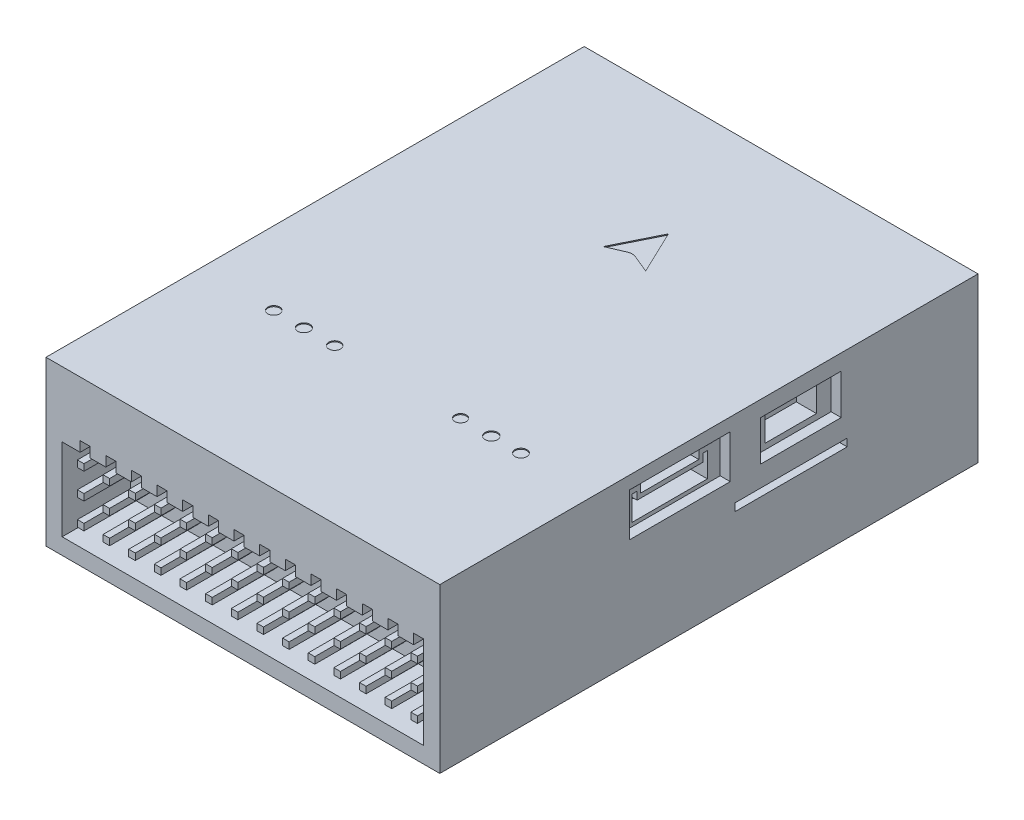
SolidWorks part; units mm, degrees
ref_plane "Front Plane" through (0, 0, 0) normal (0, 0, 1) x (1, 0, 0)
ref_plane "Top Plane" through (0, 0, 0) normal (0, 1, 0) x (1, 0, 0)
ref_plane "Right Plane" through (0, 0, 0) normal (1, 0, 0) x (0, 0, -1)
sketch "Sketch1" plane through (0, 0, 0) normal (0, 1, 0) x (1, 0, 0)
  line L0 (0, -55) -> (0, 55) construction
  line L1 (-19.5, -26.65) -> (19.5, -26.65)
  line L2 (-19.5, -26.65) -> (-19.5, 26.65)
  line L3 (-19.5, 26.65) -> (19.5, 26.65)
  line L4 (19.5, -26.65) -> (19.5, 26.65)
  line L5 (-55, 0) -> (55, 0) construction
  point P4 (0, 26.65)
  point P7 (19.5, 0)
  dimension "D1" = 39
  dimension "D2" = 53.3
extrude "Boss-Extrude1" add sketch "Sketch1" along normal mid plane 16.2
sketch "Sketch2" plane through (0, 0, 26.65) normal (0, 0, 1) x (1, 0, 0)
  line L0 (17.9, -6.5) -> (17.9, 2.64)
  line L1 (17.9, 2.64) -> (16.9, 2.64)
  line L2 (16.9, 2.64) -> (16.9, 1.64)
  line L3 (16.9, 1.64) -> (15.36, 1.64)
  line L4 (15.36, 1.64) -> (15.36, 2.64)
  line L5 (12.82, 1.64) -> (12.82, 2.64)
  line L6 (14.36, 1.64) -> (12.82, 1.64)
  line L7 (15.36, 2.64) -> (14.36, 2.64)
  line L8 (14.36, 2.64) -> (14.36, 1.64)
  line L9 (10.28, 1.64) -> (10.28, 2.64)
  line L10 (11.82, 1.64) -> (10.28, 1.64)
  line L11 (12.82, 2.64) -> (11.82, 2.64)
  line L12 (11.82, 2.64) -> (11.82, 1.64)
  line L13 (7.74, 1.64) -> (7.74, 2.64)
  line L14 (9.28, 1.64) -> (7.74, 1.64)
  line L15 (10.28, 2.64) -> (9.28, 2.64)
  line L16 (9.28, 2.64) -> (9.28, 1.64)
  line L17 (5.2, 1.64) -> (5.2, 2.64)
  line L18 (6.74, 1.64) -> (5.2, 1.64)
  line L19 (7.74, 2.64) -> (6.74, 2.64)
  line L20 (6.74, 2.64) -> (6.74, 1.64)
  line L21 (2.66, 1.64) -> (2.66, 2.64)
  line L22 (4.2, 1.64) -> (2.66, 1.64)
  line L23 (5.2, 2.64) -> (4.2, 2.64)
  line L24 (4.2, 2.64) -> (4.2, 1.64)
  line L25 (0.12, 1.64) -> (0.12, 2.64)
  line L26 (1.66, 1.64) -> (0.12, 1.64)
  line L27 (2.66, 2.64) -> (1.66, 2.64)
  line L28 (1.66, 2.64) -> (1.66, 1.64)
  line L29 (-2.42, 1.64) -> (-2.42, 2.64)
  line L30 (-0.88, 1.64) -> (-2.42, 1.64)
  line L31 (0.12, 2.64) -> (-0.88, 2.64)
  line L32 (-0.88, 2.64) -> (-0.88, 1.64)
  line L33 (-4.96, 1.64) -> (-4.96, 2.64)
  line L34 (-3.42, 1.64) -> (-4.96, 1.64)
  line L35 (-2.42, 2.64) -> (-3.42, 2.64)
  line L36 (-3.42, 2.64) -> (-3.42, 1.64)
  line L37 (-7.5, 1.64) -> (-7.5, 2.64)
  line L38 (-5.96, 1.64) -> (-7.5, 1.64)
  line L39 (-4.96, 2.64) -> (-5.96, 2.64)
  line L40 (-5.96, 2.64) -> (-5.96, 1.64)
  line L41 (-10.04, 1.64) -> (-10.04, 2.64)
  line L42 (-8.5, 1.64) -> (-10.04, 1.64)
  line L43 (-7.5, 2.64) -> (-8.5, 2.64)
  line L44 (-8.5, 2.64) -> (-8.5, 1.64)
  line L45 (-12.58, 1.64) -> (-12.58, 2.64)
  line L46 (-11.04, 1.64) -> (-12.58, 1.64)
  line L47 (-10.04, 2.64) -> (-11.04, 2.64)
  line L48 (-11.04, 2.64) -> (-11.04, 1.64)
  line L49 (-15.12, 1.64) -> (-15.12, 2.64)
  line L50 (-13.58, 1.64) -> (-15.12, 1.64)
  line L51 (-12.58, 2.64) -> (-13.58, 2.64)
  line L52 (-13.58, 2.64) -> (-13.58, 1.64)
  line L53 (17.9, -6.5) -> (-17.9, -6.5)
  line L54 (-16.12, 1.64) -> (-17.9, 1.64)
  line L55 (-15.12, 2.64) -> (-16.12, 2.64)
  line L56 (-16.12, 2.64) -> (-16.12, 1.64)
  line L57 (19.5, 8.1) -> (19.5, -8.1) construction
  line L58 (-17.66, 1.64) -> (-17.66, 2.64) [skipped]
  line L59 (-17.9, -6.5) -> (-17.9, 1.64)
  line L60 (49.3333, 77.9) -> (324.6667, 77.9) construction
  line L61 (-19.5, -8.1) -> (19.5, -8.1) construction
  dimension "D1" = 9.14
  dimension "D2" = 1
  dimension "D3" = 1.54
  dimension "D5" = 1.6
  dimension "D6" = 35.8
  dimension "1.5" = 1.6
  dimension "D4" = 14
extrude "Cut-Extrude1" cut sketch "Sketch2" against normal blind 6.75
sketch "Sketch3" plane through (0, 0, 19.9) normal (0, 0, 1) x (1, 0, 0)
  line L0 (49.3333, 77.9) -> (324.6667, 77.9) construction
  line L1 (-16.85, 0.39) -> (-16.2, 0.39)
  line L2 (-16.85, 0.39) -> (-16.85, -0.26)
  line L3 (-16.85, -0.26) -> (-16.2, -0.26)
  line L4 (-16.2, 0.39) -> (-16.2, -0.26)
  line L5 (-16.12, 1.64) -> (-17.9, 1.64) construction
  line L6 (-17.9, 1.64) -> (-17.9, -6.5) construction
  line L7 (-14.31, 0.39) -> (-14.31, -0.26)
  line L8 (-14.31, 0.39) -> (-13.66, 0.39)
  line L9 (-13.66, 0.39) -> (-13.66, -0.26)
  line L10 (-14.31, -0.26) -> (-13.66, -0.26)
  line L11 (-11.77, 0.39) -> (-11.77, -0.26)
  line L12 (-11.77, 0.39) -> (-11.12, 0.39)
  line L13 (-11.12, 0.39) -> (-11.12, -0.26)
  line L14 (-11.77, -0.26) -> (-11.12, -0.26)
  line L15 (-9.23, 0.39) -> (-9.23, -0.26)
  line L16 (-9.23, 0.39) -> (-8.58, 0.39)
  line L17 (-8.58, 0.39) -> (-8.58, -0.26)
  line L18 (-9.23, -0.26) -> (-8.58, -0.26)
  line L19 (-6.69, 0.39) -> (-6.69, -0.26)
  line L20 (-6.69, 0.39) -> (-6.04, 0.39)
  line L21 (-6.04, 0.39) -> (-6.04, -0.26)
  line L22 (-6.69, -0.26) -> (-6.04, -0.26)
  line L23 (-4.15, 0.39) -> (-4.15, -0.26)
  line L24 (-4.15, 0.39) -> (-3.5, 0.39)
  line L25 (-3.5, 0.39) -> (-3.5, -0.26)
  line L26 (-4.15, -0.26) -> (-3.5, -0.26)
  line L27 (-1.61, 0.39) -> (-1.61, -0.26)
  line L28 (-1.61, 0.39) -> (-0.96, 0.39)
  line L29 (-0.96, 0.39) -> (-0.96, -0.26)
  line L30 (-1.61, -0.26) -> (-0.96, -0.26)
  line L31 (0.93, 0.39) -> (0.93, -0.26)
  line L32 (0.93, 0.39) -> (1.58, 0.39)
  line L33 (1.58, 0.39) -> (1.58, -0.26)
  line L34 (0.93, -0.26) -> (1.58, -0.26)
  line L35 (3.47, 0.39) -> (3.47, -0.26)
  line L36 (3.47, 0.39) -> (4.12, 0.39)
  line L37 (4.12, 0.39) -> (4.12, -0.26)
  line L38 (3.47, -0.26) -> (4.12, -0.26)
  line L39 (6.01, 0.39) -> (6.01, -0.26)
  line L40 (6.01, 0.39) -> (6.66, 0.39)
  line L41 (6.66, 0.39) -> (6.66, -0.26)
  line L42 (6.01, -0.26) -> (6.66, -0.26)
  line L43 (8.55, 0.39) -> (8.55, -0.26)
  line L44 (8.55, 0.39) -> (9.2, 0.39)
  line L45 (9.2, 0.39) -> (9.2, -0.26)
  line L46 (8.55, -0.26) -> (9.2, -0.26)
  line L47 (11.09, 0.39) -> (11.09, -0.26)
  line L48 (11.09, 0.39) -> (11.74, 0.39)
  line L49 (11.74, 0.39) -> (11.74, -0.26)
  line L50 (11.09, -0.26) -> (11.74, -0.26)
  line L51 (13.63, 0.39) -> (13.63, -0.26)
  line L52 (13.63, 0.39) -> (14.28, 0.39)
  line L53 (14.28, 0.39) -> (14.28, -0.26)
  line L54 (13.63, -0.26) -> (14.28, -0.26)
  line L55 (16.17, 0.39) -> (16.17, -0.26)
  line L56 (16.17, 0.39) -> (16.82, 0.39)
  line L57 (16.82, 0.39) -> (16.82, -0.26)
  line L58 (16.17, -0.26) -> (16.82, -0.26)
  line L59 (-14.31, -2.17) -> (-14.31, -2.82)
  line L60 (-14.31, -2.17) -> (-13.66, -2.17)
  line L61 (-13.66, -2.17) -> (-13.66, -2.82)
  line L62 (-14.31, -2.82) -> (-13.66, -2.82)
  line L63 (-11.77, -2.17) -> (-11.77, -2.82)
  line L64 (-11.77, -2.17) -> (-11.12, -2.17)
  line L65 (-11.12, -2.17) -> (-11.12, -2.82)
  line L66 (-11.77, -2.82) -> (-11.12, -2.82)
  line L67 (-9.23, -2.17) -> (-9.23, -2.82)
  line L68 (-9.23, -2.17) -> (-8.58, -2.17)
  line L69 (-8.58, -2.17) -> (-8.58, -2.82)
  line L70 (-9.23, -2.82) -> (-8.58, -2.82)
  line L71 (-6.69, -2.17) -> (-6.69, -2.82)
  line L72 (-6.69, -2.17) -> (-6.04, -2.17)
  line L73 (-6.04, -2.17) -> (-6.04, -2.82)
  line L74 (-6.69, -2.82) -> (-6.04, -2.82)
  line L75 (-4.15, -2.17) -> (-4.15, -2.82)
  line L76 (-4.15, -2.17) -> (-3.5, -2.17)
  line L77 (-3.5, -2.17) -> (-3.5, -2.82)
  line L78 (-4.15, -2.82) -> (-3.5, -2.82)
  line L79 (-1.61, -2.17) -> (-1.61, -2.82)
  line L80 (-1.61, -2.17) -> (-0.96, -2.17)
  line L81 (-0.96, -2.17) -> (-0.96, -2.82)
  line L82 (-1.61, -2.82) -> (-0.96, -2.82)
  line L83 (0.93, -2.17) -> (0.93, -2.82)
  line L84 (0.93, -2.17) -> (1.58, -2.17)
  line L85 (1.58, -2.17) -> (1.58, -2.82)
  line L86 (0.93, -2.82) -> (1.58, -2.82)
  line L87 (3.47, -2.17) -> (3.47, -2.82)
  line L88 (3.47, -2.17) -> (4.12, -2.17)
  line L89 (4.12, -2.17) -> (4.12, -2.82)
  line L90 (3.47, -2.82) -> (4.12, -2.82)
  line L91 (6.01, -2.17) -> (6.01, -2.82)
  line L92 (6.01, -2.17) -> (6.66, -2.17)
  line L93 (6.66, -2.17) -> (6.66, -2.82)
  line L94 (6.01, -2.82) -> (6.66, -2.82)
  line L95 (8.55, -2.17) -> (8.55, -2.82)
  line L96 (8.55, -2.17) -> (9.2, -2.17)
  line L97 (9.2, -2.17) -> (9.2, -2.82)
  line L98 (8.55, -2.82) -> (9.2, -2.82)
  line L99 (11.09, -2.17) -> (11.09, -2.82)
  line L100 (11.09, -2.17) -> (11.74, -2.17)
  line L101 (11.74, -2.17) -> (11.74, -2.82)
  line L102 (11.09, -2.82) -> (11.74, -2.82)
  line L103 (13.63, -2.17) -> (13.63, -2.82)
  line L104 (13.63, -2.17) -> (14.28, -2.17)
  line L105 (14.28, -2.17) -> (14.28, -2.82)
  line L106 (13.63, -2.82) -> (14.28, -2.82)
  line L107 (16.17, -2.17) -> (16.17, -2.82)
  line L108 (16.17, -2.17) -> (16.82, -2.17)
  line L109 (16.82, -2.17) -> (16.82, -2.82)
  line L110 (16.17, -2.82) -> (16.82, -2.82)
  line L111 (-14.31, -4.73) -> (-14.31, -5.38)
  line L112 (-14.31, -4.73) -> (-13.66, -4.73)
  line L113 (-13.66, -4.73) -> (-13.66, -5.38)
  line L114 (-14.31, -5.38) -> (-13.66, -5.38)
  line L115 (-11.77, -4.73) -> (-11.77, -5.38)
  line L116 (-11.77, -4.73) -> (-11.12, -4.73)
  line L117 (-11.12, -4.73) -> (-11.12, -5.38)
  line L118 (-11.77, -5.38) -> (-11.12, -5.38)
  line L119 (-9.23, -4.73) -> (-9.23, -5.38)
  line L120 (-9.23, -4.73) -> (-8.58, -4.73)
  line L121 (-8.58, -4.73) -> (-8.58, -5.38)
  line L122 (-9.23, -5.38) -> (-8.58, -5.38)
  line L123 (-6.69, -4.73) -> (-6.69, -5.38)
  line L124 (-6.69, -4.73) -> (-6.04, -4.73)
  line L125 (-6.04, -4.73) -> (-6.04, -5.38)
  line L126 (-6.69, -5.38) -> (-6.04, -5.38)
  line L127 (-4.15, -4.73) -> (-4.15, -5.38)
  line L128 (-4.15, -4.73) -> (-3.5, -4.73)
  line L129 (-3.5, -4.73) -> (-3.5, -5.38)
  line L130 (-4.15, -5.38) -> (-3.5, -5.38)
  line L131 (-1.61, -4.73) -> (-1.61, -5.38)
  line L132 (-1.61, -4.73) -> (-0.96, -4.73)
  line L133 (-0.96, -4.73) -> (-0.96, -5.38)
  line L134 (-1.61, -5.38) -> (-0.96, -5.38)
  line L135 (0.93, -4.73) -> (0.93, -5.38)
  line L136 (0.93, -4.73) -> (1.58, -4.73)
  line L137 (1.58, -4.73) -> (1.58, -5.38)
  line L138 (0.93, -5.38) -> (1.58, -5.38)
  line L139 (3.47, -4.73) -> (3.47, -5.38)
  line L140 (3.47, -4.73) -> (4.12, -4.73)
  line L141 (4.12, -4.73) -> (4.12, -5.38)
  line L142 (3.47, -5.38) -> (4.12, -5.38)
  line L143 (6.01, -4.73) -> (6.01, -5.38)
  line L144 (6.01, -4.73) -> (6.66, -4.73)
  line L145 (6.66, -4.73) -> (6.66, -5.38)
  line L146 (6.01, -5.38) -> (6.66, -5.38)
  line L147 (8.55, -4.73) -> (8.55, -5.38)
  line L148 (8.55, -4.73) -> (9.2, -4.73)
  line L149 (9.2, -4.73) -> (9.2, -5.38)
  line L150 (8.55, -5.38) -> (9.2, -5.38)
  line L151 (11.09, -4.73) -> (11.09, -5.38)
  line L152 (11.09, -4.73) -> (11.74, -4.73)
  line L153 (11.74, -4.73) -> (11.74, -5.38)
  line L154 (11.09, -5.38) -> (11.74, -5.38)
  line L155 (13.63, -4.73) -> (13.63, -5.38)
  line L156 (13.63, -4.73) -> (14.28, -4.73)
  line L157 (14.28, -4.73) -> (14.28, -5.38)
  line L158 (13.63, -5.38) -> (14.28, -5.38)
  line L159 (16.17, -4.73) -> (16.17, -5.38)
  line L160 (16.17, -4.73) -> (16.82, -4.73)
  line L161 (16.82, -4.73) -> (16.82, -5.38)
  line L162 (16.17, -5.38) -> (16.82, -5.38)
  line L163 (-16.85, -2.17) -> (-16.85, -2.82)
  line L164 (-16.85, -2.17) -> (-16.2, -2.17)
  line L165 (-16.2, -2.17) -> (-16.2, -2.82)
  line L166 (-16.85, -2.82) -> (-16.2, -2.82)
  line L167 (-16.85, -4.73) -> (-16.85, -5.38)
  line L168 (-16.85, -4.73) -> (-16.2, -4.73)
  line L169 (-16.2, -4.73) -> (-16.2, -5.38)
  line L170 (-16.85, -5.38) -> (-16.2, -5.38)
  dimension "D1" = 0.65
  dimension "D2" = 0.65
  dimension "D3" = 1.25
  dimension "D4" = 1.05
  dimension "D5" = 14
  dimension "D6" = 3
extrude "Boss-Extrude2" add sketch "Sketch3" along normal offset from surface (6.29 mm away) 0.46 up to face at (0.2421, 1.8421, 26.65)
sketch "Sketch4" plane through (-19.5, 0, 0) normal (-1, 0, 0) x (0, 0, 1)
  line L0 (-255.35, 20.7333) -> (-255.35, 136.0667) construction
  line L1 (-13.428, 3.9516) -> (-6.9161, 3.9516) construction
  line L2 (-13.428, 5.2953) -> (-6.9161, 5.2953)
  line L3 (-13.428, 2.6079) -> (-6.9161, 2.6079)
  line L4 (6.6652, -1.568) -> (7.1925, -1.568)
  line L5 (-2.12, 6.3083) -> (-1.0864, 6.3083)
  line L6 (-2.12, 6.3083) -> (-2.12, 5.8535)
  line L7 (-2.12, 5.8535) -> (-1.0864, 5.8535)
  line L8 (-1.0864, 6.3083) -> (-1.0864, 5.8535)
  line L9 (6.5832, 6.3083) -> (7.6375, 6.3083)
  line L10 (6.5832, 6.3083) -> (6.5832, 5.8535)
  line L11 (6.5832, 5.8535) -> (7.6375, 5.8535)
  line L12 (7.6375, 6.3083) -> (7.6375, 5.8535)
  line L13 (-1.6032, 5.2953) -> (-1.0864, 5.2953)
  line L14 (-1.6032, 5.2953) -> (-1.6032, 2.8973)
  line L15 (-1.6032, 2.8973) -> (7.1103, 2.8973)
  line L16 (7.1103, 5.2953) -> (7.1103, 2.8973)
  line L17 (0.4641, -2.0021) -> (1.3737, -2.0021)
  line L18 (0.4641, -2.0021) -> (0.4641, -2.5189)
  line L19 (0.4641, -2.5189) -> (1.3737, -2.5189)
  line L20 (1.3737, -2.0021) -> (1.3737, -2.5189)
  line L21 (6.5832, -2.0021) -> (7.6375, -2.0021)
  line L22 (6.5832, -2.0021) -> (6.5832, -2.5189)
  line L23 (6.5832, -2.5189) -> (7.6375, -2.5189)
  line L24 (7.6375, -2.0021) -> (7.6375, -2.5189)
  line L33 (-14.2135, 1.1815) -> (-6.1305, 1.1815)
  line L34 (-14.2135, 1.1815) -> (-14.2135, -1.568)
  line L35 (-14.2135, -1.568) -> (-6.1305, -1.568)
  line L36 (-6.1305, 1.1815) -> (-6.1305, -1.568)
  line L41 (0.8703, -1.568) -> (1.3737, -1.568)
  line L42 (0.8703, -1.568) -> (0.8703, 0.8518)
  line L43 (0.8703, 0.8518) -> (7.1925, 0.8518)
  line L44 (7.1925, -1.568) -> (7.1925, 0.8518)
  line L45 (6.6652, -1.2126) -> (1.3737, -1.2126)
  line L46 (6.6652, -1.2126) -> (6.6652, -1.568)
  line L48 (1.3737, -1.2126) -> (1.3737, -1.568)
  line L49 (6.6652, 5.2953) -> (7.1103, 5.2953)
  line L50 (1.7567, -1.568) -> (6.2893, -1.568)
  line L51 (1.7567, -1.568) -> (1.7567, -2.5189)
  line L52 (1.7567, -2.5189) -> (6.2893, -2.5189)
  line L53 (6.2893, -1.568) -> (6.2893, -2.5189)
  line L55 (-1.0864, 5.2953) -> (-1.0864, 4.5845)
  line L56 (-1.0864, 4.5845) -> (6.6652, 4.5845)
  line L57 (6.6652, 5.2953) -> (6.6652, 4.5845)
  line L59 (-0.7633, 6.3083) -> (6.2893, 6.3083)
  line L60 (-0.7633, 6.3083) -> (-0.7633, 4.9703)
  line L61 (-0.7633, 4.9703) -> (6.2893, 4.9703)
  line L62 (6.2893, 6.3083) -> (6.2893, 4.9703)
  arc A0 (-13.428, 5.2953) -> (-13.428, 2.6079) centre (-13.428, 3.9516) ccw
  arc A1 (-6.9161, 2.6079) -> (-6.9161, 5.2953) centre (-6.9161, 3.9516) ccw
  point P4 (-10.172, 3.9516)
extrude "Cut-Extrude2" cut sketch "Sketch4" against normal blind 3
sketch "Sketch5" plane through (-19.5, 0, 0) normal (-1, 0, 0) x (0, 0, 1)
  line L1 (-2.8495, 6.7236) -> (8.3927, 6.7236)
  line L2 (-2.8495, 6.7236) -> (-2.8495, 2.4746)
  line L3 (-2.8495, 2.4746) -> (8.3927, 2.4746)
  line L4 (8.3927, 6.7236) -> (8.3927, 2.4746)
  line L5 (-0.3045, -3.0801) -> (8.3927, -3.0801)
  line L6 (-0.3045, -3.0801) -> (-0.3045, 1.2575)
  line L7 (-0.3045, 1.2575) -> (8.3927, 1.2575)
  line L8 (8.3927, -3.0801) -> (8.3927, 1.2575)
extrude "Cut-Extrude3" cut sketch "Sketch5" against normal blind 1
sketch "Sketch6" plane through (-16.5, 0, 0) normal (-1, 0, 0) x (0, 0, 1)
  line L0 (-13.1411, 3.9516) -> (-7.1421, 3.9516) construction
  line L1 (-13.428, 3.9516) -> (-6.9161, 3.9516) construction
  line L2 (-13.1411, 4.4327) -> (-7.1421, 4.4327)
  line L3 (-13.1411, 3.4706) -> (-7.1421, 3.4706)
  arc A0 (-13.1411, 4.4327) -> (-13.1411, 3.4706) centre (-13.1411, 3.9516) ccw
  arc A1 (-7.1421, 3.4706) -> (-7.1421, 4.4327) centre (-7.1421, 3.9516) ccw
  point P4 (-10.1416, 3.9516)
extrude "Boss-Extrude3" add sketch "Sketch6" along normal blind 2
sketch "Sketch7" plane through (19.5, 0, 0) normal (1, 0, 0) x (0, 0, -1)
  line L0 (255.35, -20.7333) -> (255.35, -136.0667) construction
  line L1 (0.4015, 5.3443) -> (0.8484, 5.3443)
  line L2 (-7.1427, 6.2913) -> (-6.1106, 6.2913)
  line L3 (-7.1427, 6.2913) -> (-7.1427, 5.8231)
  line L4 (-7.1427, 5.8231) -> (-6.1106, 5.8231)
  line L5 (-6.1106, 6.2913) -> (-6.1106, 5.8231)
  line L6 (-6.6266, 5.3443) -> (-6.1106, 5.3443)
  line L7 (-6.6266, 5.3443) -> (-6.6266, 2.9182)
  line L8 (-6.6266, 2.9182) -> (0.8484, 2.9182)
  line L9 (0.8484, 5.3443) -> (0.8484, 2.9182)
  line L10 (0.4015, 6.2913) -> (1.3592, 6.2913)
  line L11 (0.4015, 6.2913) -> (0.4015, 5.8231)
  line L12 (0.4015, 5.8231) -> (1.3592, 5.8231)
  line L13 (1.3592, 6.2913) -> (1.3592, 5.8231)
  line L15 (-6.1106, 5.3443) -> (-6.1106, 4.5675)
  line L16 (-6.1106, 4.5675) -> (0.4015, 4.5675)
  line L17 (0.4015, 5.3443) -> (0.4015, 4.5675)
  line L19 (-5.7701, 6.2913) -> (0, 6.2913)
  line L20 (-5.7701, 6.2913) -> (-5.7701, 5.0038)
  line L21 (-5.7701, 5.0038) -> (0, 5.0038)
  line L22 (0, 6.2913) -> (0, 5.0038)
  line L23 (6.5497, 5.8231) -> (11.6552, 5.8231)
  line L24 (6.5497, 5.8231) -> (6.5497, 3.117)
  line L25 (6.5497, 3.117) -> (11.6552, 3.117)
  line L26 (11.6552, 5.8231) -> (11.6552, 3.117)
  line L27 (2.5929, 0.4917) -> (13.6989, 0.4917)
  line L28 (2.5929, 0.4917) -> (2.5929, -0.2598)
  line L29 (2.5929, -0.2598) -> (13.6989, -0.2598)
  line L30 (13.6989, 0.4917) -> (13.6989, -0.2598)
extrude "Cut-Extrude4" cut sketch "Sketch7" against normal blind 3
sketch "Sketch8" plane through (19.5, 0, 0) normal (1, 0, 0) x (0, 0, -1)
  line L1 (-7.8864, 6.8306) -> (2.1133, 6.8306)
  line L2 (-7.8864, 6.8306) -> (-7.8864, 2.5486)
  line L3 (-7.8864, 2.5486) -> (2.1133, 2.5486)
  line L4 (2.1133, 6.8306) -> (2.1133, 2.5486)
  line L5 (5.1132, 6.5357) -> (13.1001, 6.5357)
  line L6 (5.1132, 6.5357) -> (5.1132, 2.5486)
  line L7 (5.1132, 2.5486) -> (13.1001, 2.5486)
  line L8 (13.1001, 6.5357) -> (13.1001, 2.5486)
extrude "Cut-Extrude5" cut sketch "Sketch8" against normal blind 1
sketch "Sketch9" plane through (0, 0, -26.65) normal (0, 0, -1) x (-1, 0, 0)
  line L0 (-49.3333, -78.4) -> (-324.6667, -78.4) construction
  line L1 (15.5763, 5.3359) -> (16.0761, 5.3359)
  line L2 (-16.5738, 6.2583) -> (-15.558, 6.2583)
  line L3 (-16.5738, 6.2583) -> (-16.5738, 5.8345)
  line L4 (-16.5738, 5.8345) -> (-15.558, 5.8345)
  line L5 (-15.558, 6.2583) -> (-15.558, 5.8345)
  line L6 (-10.3698, 6.2583) -> (-9.3468, 6.2583)
  line L7 (-10.3698, 6.2583) -> (-10.3698, 5.8345)
  line L8 (-10.3698, 5.8345) -> (-9.3468, 5.8345)
  line L9 (-9.3468, 6.2583) -> (-9.3468, 5.8345)
  line L10 (-7.3811, 6.2583) -> (-6.3215, 6.2583)
  line L11 (-7.3811, 6.2583) -> (-7.3811, 5.8345)
  line L12 (-7.3811, 5.8345) -> (-6.3215, 5.8345)
  line L13 (-6.3215, 6.2583) -> (-6.3215, 5.8345)
  line L14 (-1.1347, 6.2583) -> (-0.083, 6.2583)
  line L15 (-1.1347, 6.2583) -> (-1.1347, 5.8345)
  line L16 (-1.1347, 5.8345) -> (-0.083, 5.8345)
  line L17 (-0.083, 6.2583) -> (-0.083, 5.8345)
  line L18 (1.9225, 6.2583) -> (2.8641, 6.2583)
  line L19 (1.9225, 6.2583) -> (1.9225, 5.8345)
  line L20 (1.9225, 5.8345) -> (2.8641, 5.8345)
  line L21 (2.8641, 6.2583) -> (2.8641, 5.8345)
  line L22 (15.6474, 6.2583) -> (16.5795, 6.2583)
  line L23 (15.6474, 6.2583) -> (15.6474, 5.8345)
  line L24 (15.6474, 5.8345) -> (16.5795, 5.8345)
  line L25 (16.5795, 6.2583) -> (16.5795, 5.8345)
  line L26 (-16.5738, -2.0526) -> (-15.558, -2.0526)
  line L27 (-16.5738, -2.0526) -> (-16.5738, -2.4876)
  line L28 (-16.5738, -2.4876) -> (-15.558, -2.4876)
  line L29 (-15.558, -2.0526) -> (-15.558, -2.4876)
  line L30 (-7.8191, -2.0526) -> (-6.8513, -2.0526)
  line L31 (-7.8191, -2.0526) -> (-7.8191, -2.4876)
  line L32 (-7.8191, -2.4876) -> (-6.8513, -2.4876)
  line L33 (-6.8513, -2.0526) -> (-6.8513, -2.4876)
  line L34 (-4.8159, -2.0526) -> (-3.8631, -2.0526)
  line L35 (-4.8159, -2.0526) -> (-4.8159, -2.4876)
  line L36 (-4.8159, -2.4876) -> (-3.8631, -2.4876)
  line L37 (-3.8631, -2.0526) -> (-3.8631, -2.4876)
  line L38 (3.9038, -2.0526) -> (4.898, -2.0526)
  line L39 (3.9038, -2.0526) -> (3.9038, -2.4876)
  line L40 (3.9038, -2.4876) -> (4.898, -2.4876)
  line L41 (4.898, -2.0526) -> (4.898, -2.4876)
  line L42 (6.8449, -2.0526) -> (7.8391, -2.0526)
  line L43 (6.8449, -2.0526) -> (6.8449, -2.4876)
  line L44 (6.8449, -2.4876) -> (7.8391, -2.4876)
  line L45 (7.8391, -2.0526) -> (7.8391, -2.4876)
  line L46 (15.6474, -2.0526) -> (16.5795, -2.0526)
  line L47 (15.6474, -2.0526) -> (15.6474, -2.4876)
  line L48 (15.6474, -2.4876) -> (16.5795, -2.4876)
  line L49 (16.5795, -2.0526) -> (16.5795, -2.4876)
  line L50 (-16.0659, 5.2794) -> (-15.558, 5.2794)
  line L51 (-16.0659, 5.2794) -> (-16.0659, 2.9389)
  line L52 (-16.0659, 2.9389) -> (-9.8583, 2.9389)
  line L53 (-9.8583, 5.2794) -> (-9.8583, 2.9389)
  line L55 (-15.558, 5.2794) -> (-15.558, 4.6342)
  line L56 (-15.558, 4.6342) -> (-10.3698, 4.6342)
  line L57 (-10.3698, 5.2794) -> (-10.3698, 4.6342)
  line L58 (-6.8513, 5.3359) -> (-6.3215, 5.3359)
  line L59 (-6.8513, 5.3359) -> (-6.8513, 2.9389)
  line L60 (-6.8513, 2.9389) -> (-0.6088, 2.9389)
  line L61 (-0.6088, 5.3359) -> (-0.6088, 2.9389)
  line L63 (-6.3215, 5.3359) -> (-6.3215, 4.5853)
  line L64 (-6.3215, 4.5853) -> (-1.1347, 4.5853)
  line L65 (-1.1347, 5.3359) -> (-1.1347, 4.5853)
  line L66 (-16.0659, 0.8904) -> (-7.3352, 0.8904)
  line L67 (-16.0659, 0.8904) -> (-16.0659, -1.5854)
  line L68 (-16.0659, -1.5854) -> (-15.558, -1.5854)
  line L69 (-7.3352, 0.8904) -> (-7.3352, -1.5854)
  line L71 (-15.558, -1.5854) -> (-15.558, -0.8081)
  line L72 (-15.558, -0.8081) -> (-7.8191, -0.8081)
  line L73 (-7.8191, -1.5854) -> (-7.8191, -0.8081)
  line L74 (-4.3395, 0.8904) -> (4.4009, 0.8904)
  line L75 (-4.3395, 0.8904) -> (-4.3395, -1.5854)
  line L76 (-4.3395, -1.5854) -> (-3.8631, -1.5854)
  line L77 (4.4009, 0.8904) -> (4.4009, -1.5854)
  line L78 (-3.8631, -0.8081) -> (3.9038, -0.8081)
  line L79 (-3.8631, -0.8081) -> (-3.8631, -1.5854)
  line L81 (3.9038, -0.8081) -> (3.9038, -1.5854)
  line L82 (2.3588, 5.3359) -> (2.8641, 5.3359)
  line L83 (2.3588, 5.3359) -> (2.3588, 2.9389)
  line L84 (2.3588, 2.9389) -> (16.0761, 2.9389)
  line L85 (16.0761, 5.3359) -> (16.0761, 2.9389)
  line L87 (2.8641, 5.3359) -> (2.8641, 4.5853)
  line L88 (2.8641, 4.5853) -> (15.5763, 4.5853)
  line L89 (15.5763, 5.3359) -> (15.5763, 4.5853)
  line L90 (7.3755, -1.5854) -> (7.8391, -1.5854)
  line L91 (7.3755, -1.5854) -> (7.3755, 0.8904)
  line L92 (7.3755, 0.8904) -> (16.0761, 0.8904)
  line L93 (16.0761, -1.5854) -> (16.0761, 0.8904)
  line L95 (7.8391, -1.5854) -> (7.8391, -0.7521)
  line L96 (7.8391, -0.7521) -> (15.6474, -0.7521)
  line L97 (15.6474, -1.5854) -> (15.6474, -0.7521)
  line L98 (3.9038, -1.5854) -> (4.4009, -1.5854)
  line L99 (15.6474, -1.5854) -> (16.0761, -1.5854)
  line L100 (-10.3698, 5.2794) -> (-9.8583, 5.2794)
  line L101 (-1.1347, 5.3359) -> (-0.6088, 5.3359)
  line L102 (-7.8191, -1.5854) -> (-7.3352, -1.5854)
  line L104 (4.6656, 6.2583) -> (13.8468, 6.2583)
  line L105 (4.6656, 6.2583) -> (4.6656, 5.0122)
  line L106 (4.6656, 5.0122) -> (13.8468, 5.0122)
  line L107 (13.8468, 6.2583) -> (13.8468, 5.0122)
  line L108 (8.2256, -2.4876) -> (15.2521, -2.4876)
  line L109 (8.2256, -2.4876) -> (8.2256, -1.2335)
  line L110 (8.2256, -1.2335) -> (15.2521, -1.2335)
  line L111 (15.2521, -2.4876) -> (15.2521, -1.2335)
  line L112 (-3.5007, -2.4876) -> (3.5258, -2.4876)
  line L113 (-3.5007, -2.4876) -> (-3.5007, -1.2335)
  line L114 (-3.5007, -1.2335) -> (3.5258, -1.2335)
  line L115 (3.5258, -2.4876) -> (3.5258, -1.2335)
  line L116 (-5.9989, 6.2583) -> (-1.3927, 6.2583)
  line L117 (-5.9989, 6.2583) -> (-5.9989, 5.0122)
  line L118 (-5.9989, 5.0122) -> (-1.3927, 5.0122)
  line L119 (-1.3927, 6.2583) -> (-1.3927, 5.0122)
  line L120 (-15.2537, 6.2583) -> (-10.6622, 6.2583)
  line L121 (-15.2537, 6.2583) -> (-15.2537, 5.0122)
  line L122 (-15.2537, 5.0122) -> (-10.6622, 5.0122)
  line L123 (-10.6622, 6.2583) -> (-10.6622, 5.0122)
  line L124 (-15.2537, -1.2335) -> (-8.1834, -1.2335)
  line L125 (-15.2537, -1.2335) -> (-15.2537, -2.4876)
  line L126 (-15.2537, -2.4876) -> (-8.1834, -2.4876)
  line L127 (-8.1834, -1.2335) -> (-8.1834, -2.4876)
extrude "Cut-Extrude6" cut sketch "Sketch9" against normal blind 3
sketch "Sketch10" plane through (0, 0, -26.65) normal (0, 0, -1) x (-1, 0, 0)
  line L1 (-17.3071, 6.8211) -> (-8.6929, 6.8211)
  line L2 (-17.3071, 6.8211) -> (-17.3071, 2.514)
  line L3 (-17.3071, 2.514) -> (-8.6929, 2.514)
  line L4 (-8.6929, 6.8211) -> (-8.6929, 2.514)
  line L5 (-8.0138, 6.8211) -> (0.5825, 6.8211)
  line L6 (-8.0138, 6.8211) -> (-8.0138, 2.514)
  line L7 (-8.0138, 2.514) -> (0.5825, 2.514)
  line L8 (0.5825, 6.8211) -> (0.5825, 2.514)
  line L9 (1.2616, 6.8211) -> (17.3462, 6.8211)
  line L10 (1.2616, 6.8211) -> (1.2616, 2.4068)
  line L11 (1.2616, 2.4068) -> (17.3462, 2.4068)
  line L12 (17.3462, 6.8211) -> (17.3462, 2.4068)
  line L13 (-17.3071, 1.263) -> (-6.173, 1.263)
  line L14 (-17.3071, 1.263) -> (-17.3071, -3.1514)
  line L15 (-17.3071, -3.1514) -> (-6.173, -3.1514)
  line L16 (-6.173, 1.263) -> (-6.173, -3.1514)
  line L17 (-5.3331, 1.263) -> (5.5866, 1.263)
  line L18 (-5.3331, 1.263) -> (-5.3331, -3.0441)
  line L19 (-5.3331, -3.0441) -> (5.5866, -3.0441)
  line L20 (5.5866, 1.263) -> (5.5866, -3.0441)
  line L21 (6.2657, -3.0441) -> (17.3462, -3.0441)
  line L22 (6.2657, -3.0441) -> (6.2657, 1.263)
  line L23 (6.2657, 1.263) -> (17.3462, 1.263)
  line L24 (17.3462, -3.0441) -> (17.3462, 1.263)
extrude "Cut-Extrude7" cut sketch "Sketch10" against normal blind 1
sketch "Sketch11" plane through (0, 8.1, 0) normal (0, 1, 0) x (1, 0, 0)
  line L0 (49.3333, 255.35) -> (324.6667, 255.35) construction
  line L1 (0.7387, 14.7547) -> (-1.3997, 10.4391)
  line L3 (2.7993, 10.4391) -> (0.7387, 14.7547)
  line L4 (-1.3997, 10.4391) -> (0.2767, 11.1574)
  line L5 (1.053, 11.1621) -> (2.7993, 10.4391)
  arc A0 (1.053, 11.1621) -> (0.2767, 11.1574) centre (0.6705, 10.2382) ccw
  circle A1 centre (-12.2397, -11.3539) radius 0.5865
  circle A2 centre (-9.2571, -11.3539) radius 0.6032
  circle A3 centre (-6.2076, -11.3539) radius 0.5865
  circle A4 centre (6.2587, -11.3539) radius 0.5697
  circle A5 centre (9.3083, -11.3539) radius 0.6218
  circle A6 centre (12.2405, -11.3539) radius 0.5981
  dimension "D1" = 1
extrude "Cut-Extrude8" cut sketch "Sketch11" against normal blind 0.1
